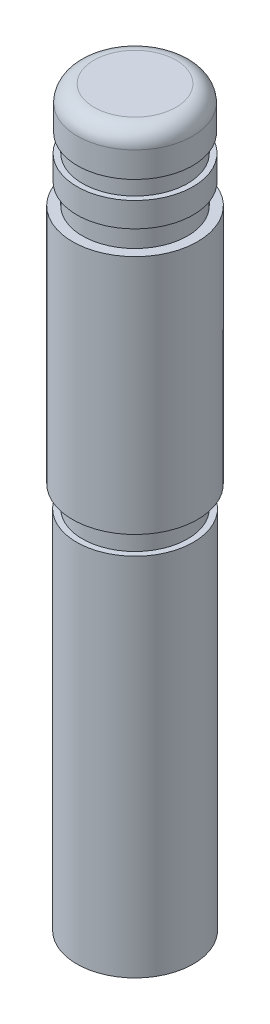
SolidWorks part; units mm, degrees
ref_plane "前视基准面" through (0, 0, 0) normal (0, 0, 1) x (1, 0, 0)
ref_plane "上视基准面" through (0, 0, 0) normal (0, 1, 0) x (1, 0, 0)
ref_plane "右视基准面" through (0, 0, 0) normal (1, 0, 0) x (0, 0, -1)
sketch "草图1" plane through (0, 0, 0) normal (1, 0, 0) x (0, 0, -1)
  line L0 (0, 0) -> (0, 93.9292) construction
  line L1 (-7, 0) -> (0, 0)
  line L2 (-4.9141, 88) -> (0, 88)
  line L3 (0, 88) -> (0, 0)
  line L16 (-6.9141, 82.9333) -> (-6.9141, 86)
  line L17 (-6.3094, 82.9333) -> (-6.9141, 82.9333)
  line L18 (-6.3094, 80.781) -> (-6.3094, 82.9333)
  line L19 (-6.9606, 80.781) -> (-6.3094, 80.781)
  line L20 (-6.9606, 77.8291) -> (-6.9606, 80.781)
  line L21 (-6.3094, 77.8291) -> (-6.9606, 77.8291)
  line L22 (-6.3094, 75.3284) -> (-6.3094, 77.8291)
  line L23 (-7.5, 75.3284) -> (-6.3094, 75.3284)
  line L24 (-7.5, 46.4472) -> (-7.5, 75.3284)
  line L25 (-6.3094, 46.4472) -> (-7.5, 46.4472)
  line L26 (-6.3094, 43.8356) -> (-6.3094, 46.4472)
  line L27 (-7, 43.8356) -> (-6.3094, 43.8356)
  line L28 (-7, 0) -> (-7, 43.8356)
  arc A0 (-4.9141, 88) -> (-6.9141, 86) centre (-4.9141, 86) ccw
  point P36 (-6.9141, 88)
  dimension "D4" = 2
  dimension "D1" = 7
  dimension "D2" = 7.5
revolve "旋转4" add sketch "草图1" angle 360 about L0
